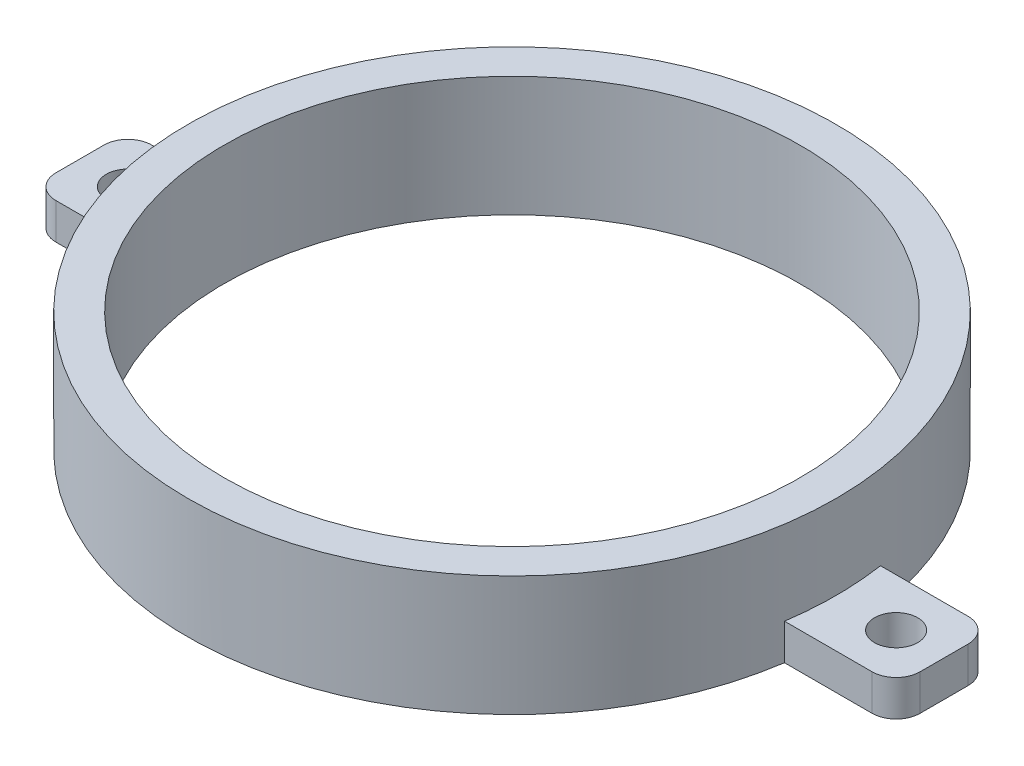
SolidWorks part; units mm, degrees
ref_plane "Front Plane" through (0, 0, 0) normal (0, 0, 1) x (1, 0, 0)
ref_plane "Top Plane" through (0, 0, 0) normal (0, 1, 0) x (1, 0, 0)
ref_plane "Right Plane" through (0, 0, 0) normal (1, 0, 0) x (0, 0, -1)
sketch "Sketch1" plane through (0, 0, 0) normal (0, 1, 0) x (1, 0, 0)
  circle A0 centre (0, 0) radius 24
  circle A1 centre (0, 0) radius 27
  dimension "D1" = 48
  dimension "D2" = 3
extrude "Boss-Extrude1" add sketch "Sketch1" along normal blind 10
ref_plane "Plane1" through (-26, 0, 0) normal (1, 0, 0) x (0, 0, -1)
sketch "Sketch3" plane through (0, 0, 0) normal (0, 1, 0) x (1, 0, 0)
  line L0 (0, 0) -> (-41.3497, 0) construction
  line L1 (-24, 0) -> (-24, 4)
  line L2 (-24, 4) -> (-34, 4)
  line L3 (-36, 2) -> (-36, -2)
  line L4 (-34, -4) -> (-24, -4)
  line L5 (-24, -4) -> (-24, 0)
  circle A2 centre (0, 0) radius 24 construction
  circle A3 centre (0, 0) radius 24 construction
  circle A4 centre (-32, 0) radius 1.8
  arc A5 (-36, 2) -> (-34, 4) centre (-34, 2) cw
  arc A6 (-34, -4) -> (-36, -2) centre (-34, -2) cw
  dimension "D3" = 3.6
  dimension "D4" = 8
  dimension "D5" = 2
  dimension "D6" = 2
  dimension "D1" = 8
  dimension "D2" = 12
extrude "Boss-Extrude2" add sketch "Sketch3" along normal blind 3
mirror "Mirror1" about plane through (0, 0, 0) normal (1, 0, 0) of "Boss-Extrude2"
